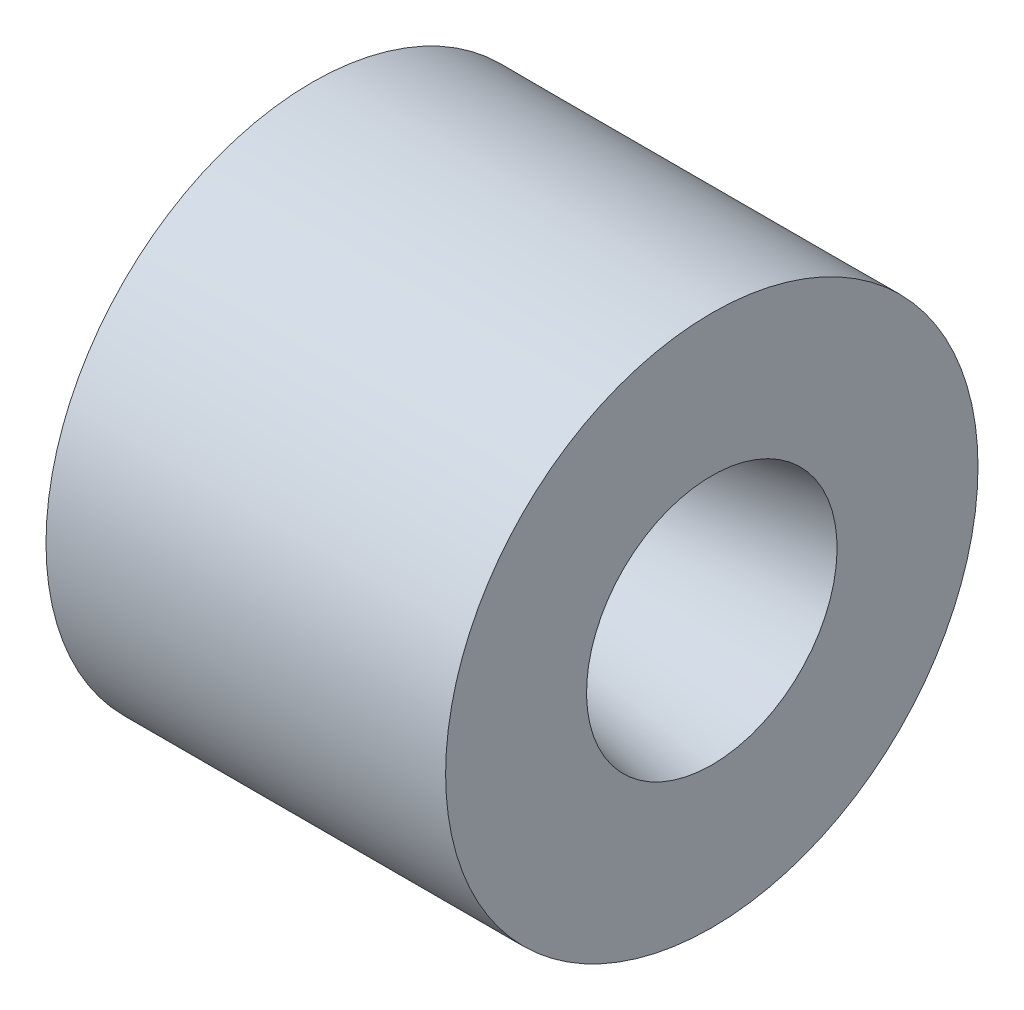
SolidWorks part; units mm, degrees
material "Malleable Cast Iron"
ref_plane "Front Plane" through (0, 0, 0) normal (0, 0, 1) x (1, 0, 0)
ref_plane "Top Plane" through (0, 0, 0) normal (0, 1, 0) x (1, 0, 0)
ref_plane "Right Plane" through (0, 0, 0) normal (1, 0, 0) x (0, 0, -1)
sketch "Sketch2" plane through (0, 0, 0) normal (0, 0, 1) x (1, 0, 0)
  line L0 (0.017, 0) -> (9533.1825, 0) construction
  line L1 (-0.0434, 16.9999) -> (-0.0434, 3.5)
  line L2 (-0.0434, 3.5) -> (25.4774, 8)
  line L3 (25.4774, 8) -> (25.4774, 17)
  line L4 (25.4774, 17) -> (-0.0434, 16.9999)
  point P7 (0, 0)
  point P8 (0, 0)
  point P9 (25.0976, 17)
  point P10 (0, 0)
  point P11 (0, 0)
  point P12 (0, 0)
  point P13 (26.4506, 17)
  point P14 (0, 0)
  point P15 (0, 0)
  point P16 (22.7559, 17)
  point P17 (25.722, 17)
  dimension "D1" = 3.5
  dimension "D2" = 17
  dimension "D3" = 8
  dimension "D4" = 10
  dimension "D5" = 17
revolve "Revolve1" add sketch "Sketch2" angle 360 about L0
